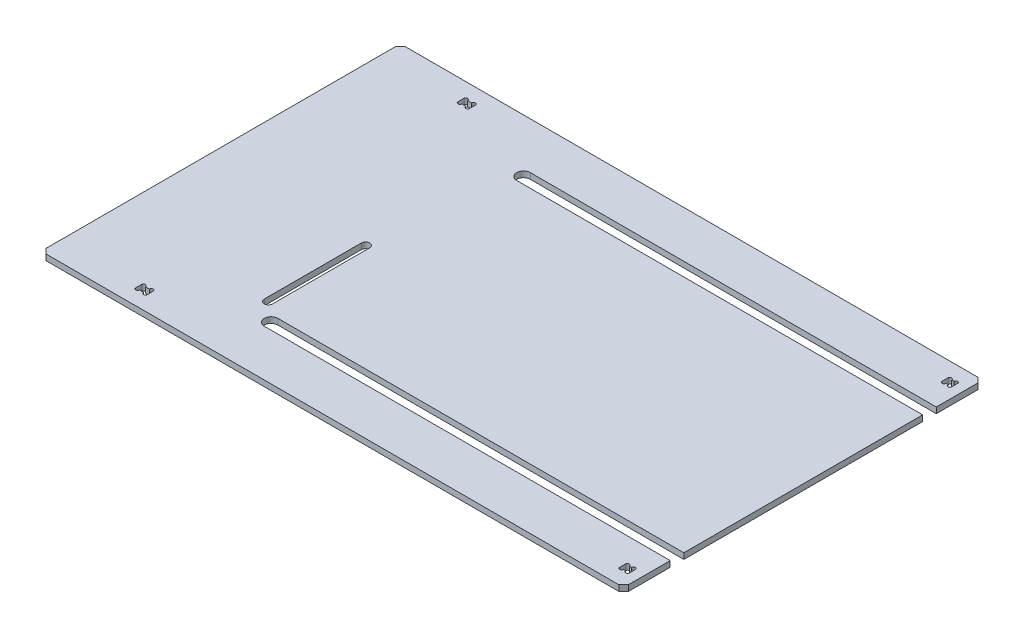
SolidWorks part; units mm, degrees
ref_plane "정면" through (0, 0, 0) normal (0, 0, 1) x (1, 0, 0)
ref_plane "윗면" through (0, 0, 0) normal (0, 1, 0) x (1, 0, 0)
ref_plane "우측면" through (0, 0, 0) normal (1, 0, 0) x (0, 0, -1)
sketch "스케치1" plane through (0, 0, 0) normal (0, 1, 0) x (1, 0, 0)
  line L1 (0, 0) -> (300, 0)
  line L2 (0, 0) -> (0, 185)
  line L3 (0, 185) -> (300, 185)
  line L4 (300, 0) -> (300, 185)
  dimension "D1" = 185
  dimension "D2" = 300
extrude "보스-돌출1" add sketch "스케치1" along normal blind 3
sketch "스케치2" plane through (0, 3, 0) normal (0, 1, 0) x (1, 0, 0)
  line L0 (92.9, 61.1066) -> (93.0904, 61.1066) construction
  line L1 (92.9, 58.6066) -> (92.9, 63.6066) construction
  line L3 (78.8, 61.1066) -> (78.8, 86.1066)
  line L4 (78.8, 36.1066) -> (83.1, 36.1066)
  line L5 (78.8, 36.1066) -> (78.8, 61.1066)
  line L6 (78.8, 86.1066) -> (83.1, 86.1066)
  line L7 (83.1, 36.1066) -> (83.1, 86.1066)
  line L8 (80, 81.2292) -> (80, 83.4866) construction
  line L10 (80.9, 81.2292) -> (80.9, 83.4866) construction
  dimension "D1" = 1.2
  dimension "D2" = 2.2
  dimension "D3" = 25
  dimension "D4" = 25
extrude "컷-돌출1" cut sketch "스케치2" against normal blind 10
sketch "스케치3" plane through (0, 3, 0) normal (0, 1, 0) x (1, 0, 0)
  line L0 (83.1, 86.1066) -> (78.8, 86.1066) construction
  line L1 (78.8, 36.1066) -> (83.1, 36.1066) construction
  circle A0 centre (80.95, 86.1066) radius 2.15
  circle A1 centre (80.95, 36.1066) radius 2.15
extrude "컷-돌출2" cut sketch "스케치3" against normal blind 10
sketch "스케치4" plane through (0, 3, 0) normal (0, 1, 0) x (1, 0, 0)
  line L0 (98.2962, 160) -> (115.1566, 160) construction
  line L1 (300, 161) -> (90.9, 161)
  line L2 (300, 161) -> (300, 154)
  line L3 (300, 154) -> (90.9, 154)
  line L4 (90.9, 161) -> (90.9, 154)
  line L5 (90.9, 24) -> (300, 24)
  line L6 (90.9, 24) -> (90.9, 31)
  line L7 (90.9, 31) -> (300, 31)
  line L8 (300, 24) -> (300, 31)
  line L9 (98.2962, 155) -> (115.1566, 155) construction
  line L10 (98.2962, 30) -> (115.1566, 30) construction
  line L13 (300, 0) -> (300, 185) construction
  dimension "D1" = 1
  dimension "D2" = 1
  dimension "D3" = 1
  dimension "D4" = 10
extrude "컷-돌출3" cut sketch "스케치4" against normal blind 10
sketch "스케치5" plane through (0, 3, 0) normal (0, 1, 0) x (1, 0, 0)
  line L0 (90.9, 161) -> (90.9, 154) construction
  line L3 (90.9, 31) -> (90.9, 24) construction
  circle A0 centre (90.9, 157.5) radius 3.5
  circle A3 centre (90.9, 27.5) radius 3.5
extrude "컷-돌출5" cut sketch "스케치5" against normal blind 10
chamfer "모따기1" distance 2.5 angle 45 4 edges at (0, 1.5, 0) (0, 1.5, -185) (300, 1.5, 0) (300, 1.5, -185)
sketch "스케치9" plane through (0, 0, 0) normal (0, -1, 0) x (1, 0, 0)
  line L0 (300, -92.5) -> (232.8705, -92.5) construction
  line L1 (290, -174) -> (295, -174)
  line L2 (290, -174) -> (290, -177)
  line L3 (290, -177) -> (295, -177)
  line L4 (295, -174) -> (295, -177)
  line L5 (46.7, -174) -> (40.7, -174)
  line L6 (46.7, -174) -> (46.7, -177)
  line L7 (46.7, -177) -> (40.7, -177)
  line L8 (40.7, -174) -> (40.7, -177)
  line L9 (300, -31) -> (300, -154) construction
  line L10 (40.7, -11) -> (40.7, -8)
  line L11 (46.7, -8) -> (40.7, -8)
  line L12 (46.7, -11) -> (46.7, -8)
  line L13 (46.7, -11) -> (40.7, -11)
  line L14 (295, -11) -> (295, -8)
  line L15 (290, -8) -> (295, -8)
  line L16 (290, -11) -> (290, -8)
  line L17 (290, -11) -> (295, -11)
  dimension "D1" = 6
  dimension "D2" = 5
extrude "컷-돌출9" cut sketch "스케치9" against normal blind 10
sketch "스케치10" plane through (0, 3, 0) normal (0, 1, 0) x (1, 0, 0)
  line L0 (295, 174) -> (290, 174) construction
  line L1 (290, 177) -> (295, 177) construction
  line L2 (46.7, 174) -> (40.7, 174) construction
  line L3 (40.7, 177) -> (46.7, 177) construction
  line L4 (0, 92.5) -> (300, 92.5) construction
  line L5 (0, 182.5) -> (0, 2.5) construction
  line L6 (300, 31) -> (300, 154) construction
  circle A0 centre (294.034, 174) radius 0.966
  circle A1 centre (290.966, 174) radius 0.966
  circle A2 centre (290.966, 177) radius 0.966
  circle A3 centre (294.034, 177) radius 0.966
  circle A4 centre (41.666, 174) radius 0.966
  circle A5 centre (41.666, 177) radius 0.966
  circle A6 centre (45.734, 177) radius 0.966
  circle A7 centre (45.734, 174) radius 0.966
  circle A8 centre (45.734, 11) radius 0.966
  circle A9 centre (45.734, 8) radius 0.966
  circle A10 centre (41.666, 8) radius 0.966
  circle A11 centre (41.666, 11) radius 0.966
  circle A12 centre (294.034, 8) radius 0.966
  circle A13 centre (290.966, 8) radius 0.966
  circle A14 centre (290.966, 11) radius 0.966
  circle A15 centre (294.034, 11) radius 0.966
extrude "컷-돌출10" cut sketch "스케치10" against normal blind 10
